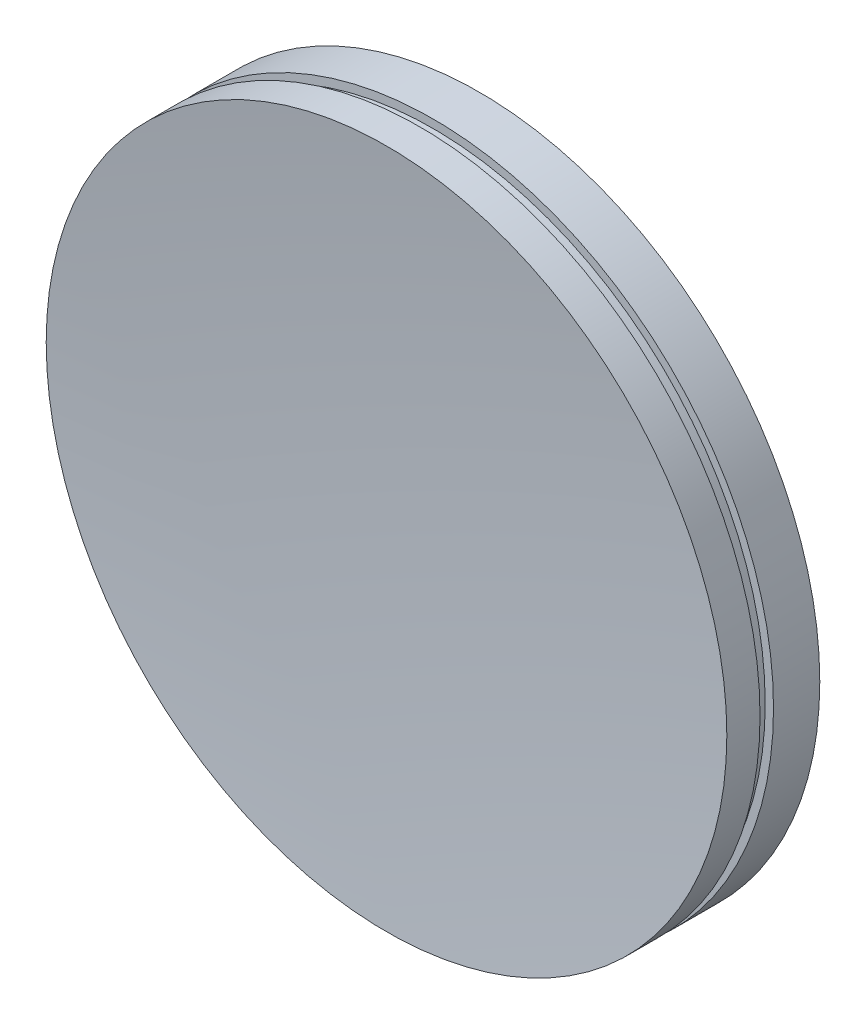
SolidWorks part; units mm, degrees
material "Verre"
ref_plane "Plan de face" through (0, 0, 0) normal (0, 0, 1) x (1, 0, 0)
ref_plane "Plan de dessus" through (0, 0, 0) normal (0, 1, 0) x (1, 0, 0)
ref_plane "Plan de droite" through (0, 0, 0) normal (1, 0, 0) x (0, 0, -1)
sketch "Esquisse1" plane through (0, 0, 0) normal (0, 0, 1) x (1, 0, 0)
  circle A0 centre (0, 0) radius 205
  dimension "D1" = 410
extrude "Boss.-Extru.1" add sketch "Esquisse1" along normal blind 56
sketch "Esquisse2" plane through (0, 0, 0) normal (0, 1, 0) x (1, 0, 0)
  line L0 (0, 0) -> (0, -856) construction
  line L1 (-205, -56) -> (205, -56) construction
  line L2 (0, -2095.7242) -> (0, -45.7242)
  line L3 (0, -2095.7242) -> (2050, -2095.7242)
  arc A0 (2050, -2095.7242) -> (0, -45.7242) centre (0, -2095.7242) ccw
  dimension "D1" = 4100
  dimension "D2" = 800
revolve "Enlèvement de matière-Révolution6" cut sketch "Esquisse2" angle 360 about L0
sketch "Esquisse3" plane through (0, 0, 0) normal (0, 1, 0) x (1, 0, 0)
  line L0 (205, -56) -> (205, 0) construction
  line L1 (205, -36) -> (200, -36)
  line L2 (205, -36) -> (205, -27.88)
  line L3 (205, -27.88) -> (200, -27.88)
  line L4 (200, -36) -> (200, -27.88)
  line L5 (205, -56) -> (-205, -56) construction
  dimension "D1" = 20
  dimension "D2" = 8.12
  dimension "D3" = 5
revolve "Enlèvement de matière-Révolution7" cut sketch "Esquisse3" angle 360 about L2
